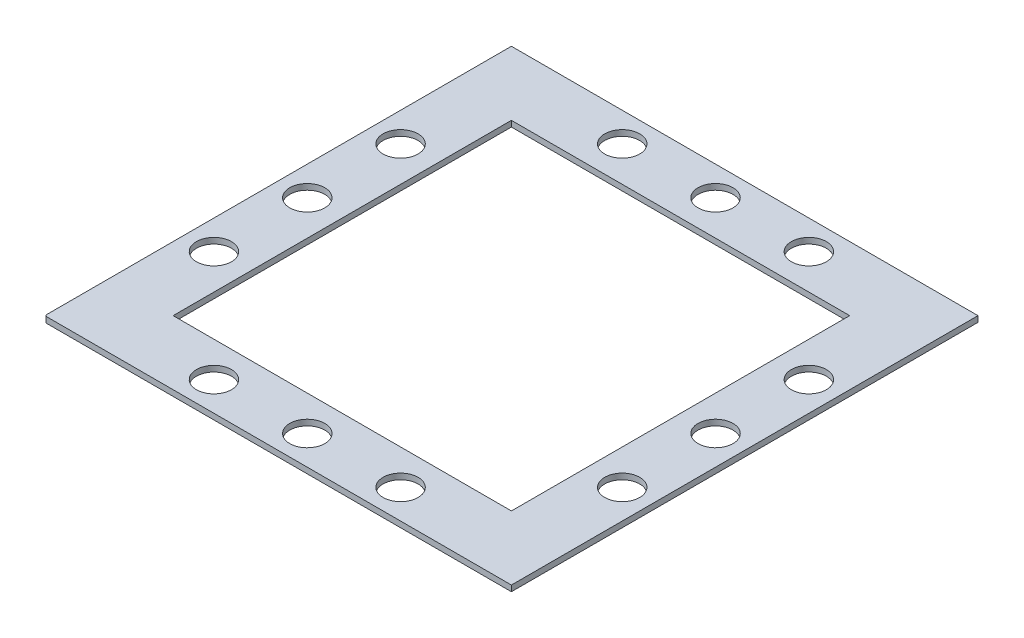
SolidWorks part; units mm, degrees
ref_plane "Alzado" through (0, 0, 0) normal (0, 0, 1) x (1, 0, 0)
ref_plane "Planta" through (0, 0, 0) normal (0, 1, 0) x (1, 0, 0)
ref_plane "Vista lateral" through (0, 0, 0) normal (1, 0, 0) x (0, 0, -1)
sketch "Croquis1" plane through (0, 0, 0) normal (0, 1, 0) x (1, 0, 0)
  line L0 (0, 0) -> (29, 29) construction
  line L1 (0, 0) -> (29, 0)
  line L2 (0, 0) -> (0, 29)
  line L3 (0, 29) -> (29, 29)
  line L4 (29, 0) -> (29, 29)
  line L5 (-5.5, -5.5) -> (34.5, -5.5)
  line L6 (-5.5, -5.5) -> (-5.5, 34.5)
  line L7 (-5.5, 34.5) -> (34.5, 34.5)
  line L8 (34.5, -5.5) -> (34.5, 34.5)
  line L9 (-5.5, 34.5) -> (34.5, -5.5) construction
  line L10 (-7.9749, 36.9749) -> (-5.5, 34.5) construction
  line L13 (14.5, 14.5) -> (0, 14.5) construction
  line L14 (14.5, -0.5) -> (14.5, -5.5) construction
  line L15 (-0.5, 29.5) -> (29.5, 29.5) construction
  line L16 (-0.5, 29.5) -> (-0.5, -0.5) construction
  line L17 (-0.5, -0.5) -> (29.5, -0.5) construction
  line L18 (29.5, 29.5) -> (29.5, -0.5) construction
  line L19 (-0.5, 29.5) -> (29.5, -0.5) construction
  line L20 (-0.5, -0.5) -> (29.5, 29.5) construction
  line L21 (6.5, -3) -> (14.5, -3) construction
  line L22 (14.5, -3) -> (22.5, -3) construction
  circle A4 centre (6.5, -3) radius 1.5
  circle A5 centre (22.5, -3) radius 1.5
  circle A9 centre (-3, 22.5) radius 1.5
  circle A10 centre (-3, 6.5) radius 1.5
  arc A12 (-5.5, -5.3814) -> (-5.3985, -5.5) centre (-2.7911, -3.1651) ccw
  circle A14 centre (22.5, 32) radius 1.5
  circle A17 centre (6.5, 32) radius 1.5
  circle A19 centre (32, 6.5) radius 1.5
  circle A20 centre (32, 22.5) radius 1.5
  circle A22 centre (14.5, -3) radius 1.5
  circle A23 centre (-3, 14.5) radius 1.5
  circle A24 centre (14.5, 32) radius 1.5
  circle A25 centre (32, 14.5) radius 1.5
  point P9 (14.5, 14.5)
  point P10 (14.5, 14.5)
  dimension "D3" = 4
  dimension "D7" = 3
  dimension "D1" = 29
  dimension "D2" = 40
  dimension "D5" = 3.5
  dimension "D6" = 30
  dimension "D8" = 8
  dimension "D9" = 4
extrude "Saliente-Extruir1" add sketch "Croquis1" along normal blind 0.5
